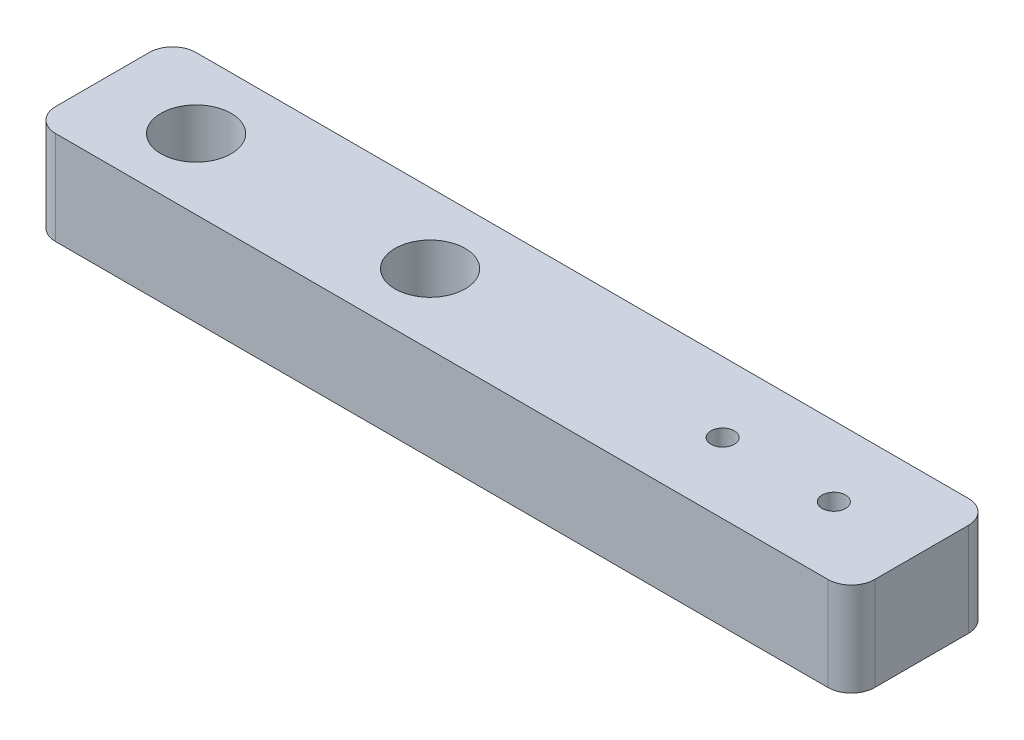
SolidWorks part; units mm, degrees
ref_plane "Front Plane" through (0, 0, 0) normal (0, 0, 1) x (1, 0, 0)
ref_plane "Top Plane" through (0, 0, 0) normal (0, 1, 0) x (1, 0, 0)
ref_plane "Right Plane" through (0, 0, 0) normal (1, 0, 0) x (0, 0, -1)
sketch "Sketch1" plane through (0, 0, 0) normal (0, 1, 0) x (1, 0, 0)
  line L1 (-35, -6) -> (35, -6)
  line L2 (-35, -6) -> (-35, 6)
  line L3 (-35, 6) -> (35, 6)
  line L4 (35, -6) -> (35, 6)
  line L5 (-35, -6) -> (35, 6) construction
  line L6 (-35, 6) -> (35, -6) construction
  point P0 (0, 0)
  dimension "D1" = 70
  dimension "D2" = 12
extrude "Boss-Extrude1" add sketch "Sketch1" along normal blind 8
sketch "Sketch2" plane through (0, 8, 0) normal (0, 1, 0) x (1, 0, 0)
  line L0 (-35, 6) -> (-35, -6) construction
  line L1 (18, 0) -> (27.5, 0) construction
  circle A0 centre (-27, 0) radius 3
  circle A1 centre (-7, 0) radius 3
  circle A2 centre (18, 0) radius 1
  circle A3 centre (27.5, 0) radius 1
  dimension "D2" = 6
  dimension "D4" = 2
  dimension "D1" = 20
  dimension "D3" = 8
  dimension "D5" = 9.5
  dimension "D6" = 34.5
extrude "Cut-Extrude1" cut sketch "Sketch2" against normal through all
fillet "Fillet1" radius 2 4 edges at (-35, 4, -6) (35, 4, -6) (35, 4, 6) (-35, 4, 6)
